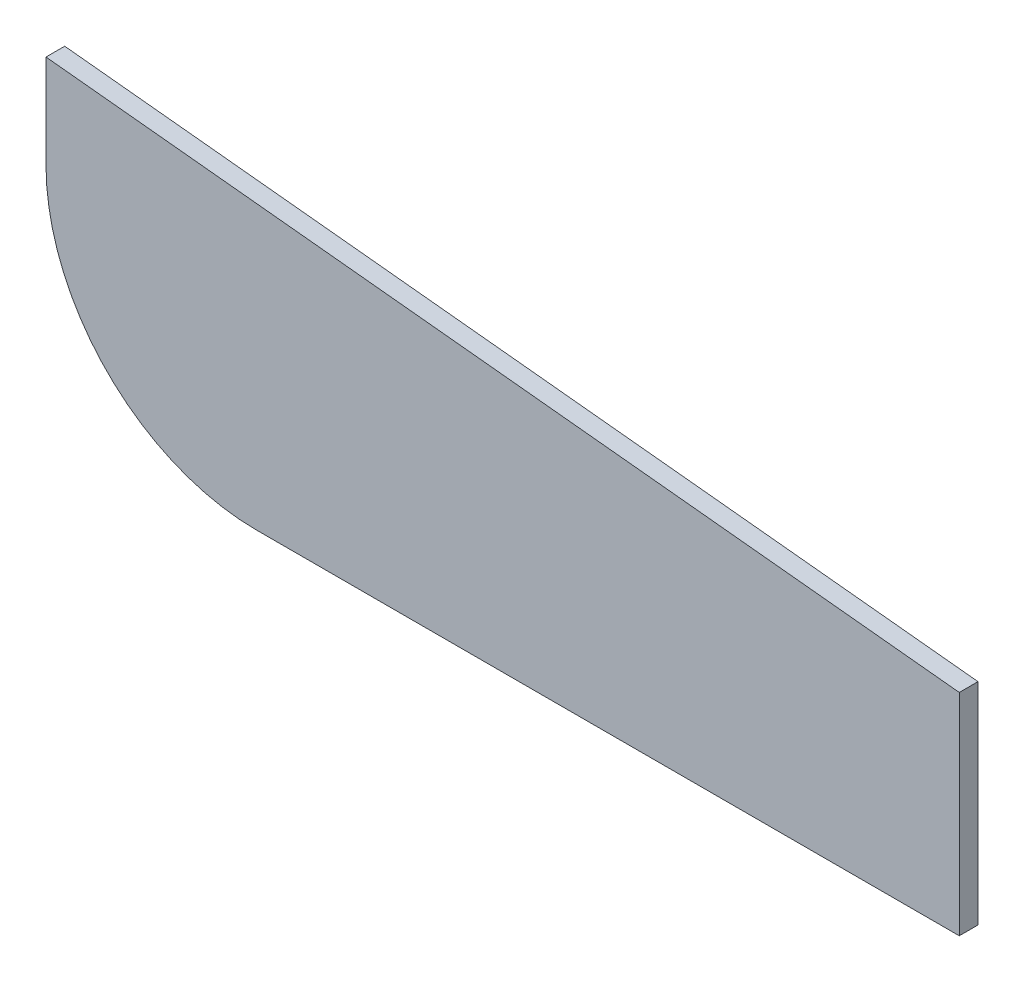
SolidWorks part; units mm, degrees
ref_plane "Front Plane" through (0, 0, 0) normal (0, 0, 1) x (1, 0, 0)
ref_plane "Top Plane" through (0, 0, 0) normal (0, 1, 0) x (1, 0, 0)
ref_plane "Right Plane" through (0, 0, 0) normal (1, 0, 0) x (0, 0, -1)
sketch "Sketch1" plane through (0, 0, 0) normal (0, 1, 0) x (1, 0, 0)
  line L1 (-97.5, -2) -> (97.5, -2)
  line L2 (-97.5, -2) -> (-97.5, 2)
  line L3 (-97.5, 2) -> (97.5, 2)
  line L4 (97.5, -2) -> (97.5, 2)
  line L5 (-97.5, -2) -> (97.5, 2) construction
  line L6 (-97.5, 2) -> (97.5, -2) construction
  point P0 (0, 0)
  dimension "D1" = 4
  dimension "D2" = 195
extrude "Boss-Extrude1" add sketch "Sketch1" against normal blind 65
sketch "Sketch2" plane through (0, 0, 2) normal (0, 0, 1) x (1, 0, 0)
  line L0 (-97.5, 0) -> (97.5, -20)
  line L1 (97.5, -65) -> (97.5, 0) construction
  line L2 (97.5, -20) -> (97.5, 0)
  line L3 (97.5, 0) -> (-97.5, 0)
  line L4 (-97.5, -65) -> (97.5, -65) construction
  dimension "D1" = 45
extrude "Cut-Extrude1" cut sketch "Sketch2" against normal blind 10
sketch "Sketch3" plane through (0, 0, 2) normal (0, 0, 1) x (1, 0, 0)
  line L0 (-97.5, -65) -> (97.5, -65) construction
  line L1 (-97.5, -20) -> (-97.5, -65)
  line L2 (-97.5, -65) -> (-52.5, -65)
  arc A0 (-97.5, -20) -> (-52.5, -65) centre (-52.5, -20) ccw
  dimension "D1" = 45
extrude "Cut-Extrude2" cut sketch "Sketch3" against normal blind 10
